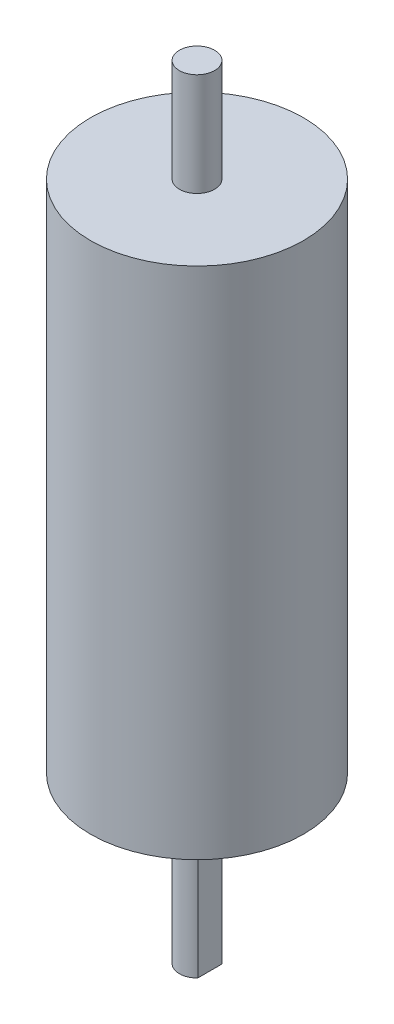
SolidWorks part; units mm, degrees
ref_plane "Alzado" through (0, 0, 0) normal (0, 0, 1) x (1, 0, 0)
ref_plane "Planta" through (0, 0, 0) normal (0, 1, 0) x (1, 0, 0)
ref_plane "Vista lateral" through (0, 0, 0) normal (1, 0, 0) x (0, 0, -1)
sketch "Croquis1" plane through (0, 0, 0) normal (0, 1, 0) x (1, 0, 0)
  circle A0 centre (0, 0) radius 14.5
  dimension "D1" = 29
extrude "Saliente-Extruir1" add sketch "Croquis1" along normal mid plane 70
sketch "Croquis2" plane through (0, 0, 0) normal (0, 1, 0) x (1, 0, 0)
  circle A0 centre (0, 0) radius 2.4
  dimension "D1" = 4.8
extrude "Saliente-Extruir2" add sketch "Croquis2" along normal mid plane 86
sketch "Croquis3" plane through (0, -43, 0) normal (0, -1, 0) x (1, 0, 0)
  line L0 (-1.75, 1.6424) -> (-1.75, -1.6424)
  line L1 (0, 0) -> (0, 2.4) construction
  line L2 (1.75, 1.6424) -> (1.75, -1.6424)
  circle A0 centre (0, 0) radius 2.4 construction
  arc A1 (-1.75, -1.6424) -> (1.75, -1.6424) centre (0, 0) ccw
  arc A2 (1.75, 1.6424) -> (-1.75, 1.6424) centre (0, 0) ccw
  dimension "D1" = 3.5
extrude "Saliente-Extruir3" add sketch "Croquis3" along normal blind 14.5
sketch "Croquis4" plane through (0, 43, 0) normal (0, 1, 0) x (1, 0, 0)
  circle A1 centre (0, 0) radius 2.4
  circle A2 centre (0, 0) radius 2.4
  dimension "D1" = 0
extrude "Saliente-Extruir4" add sketch "Croquis4" along normal blind 6
